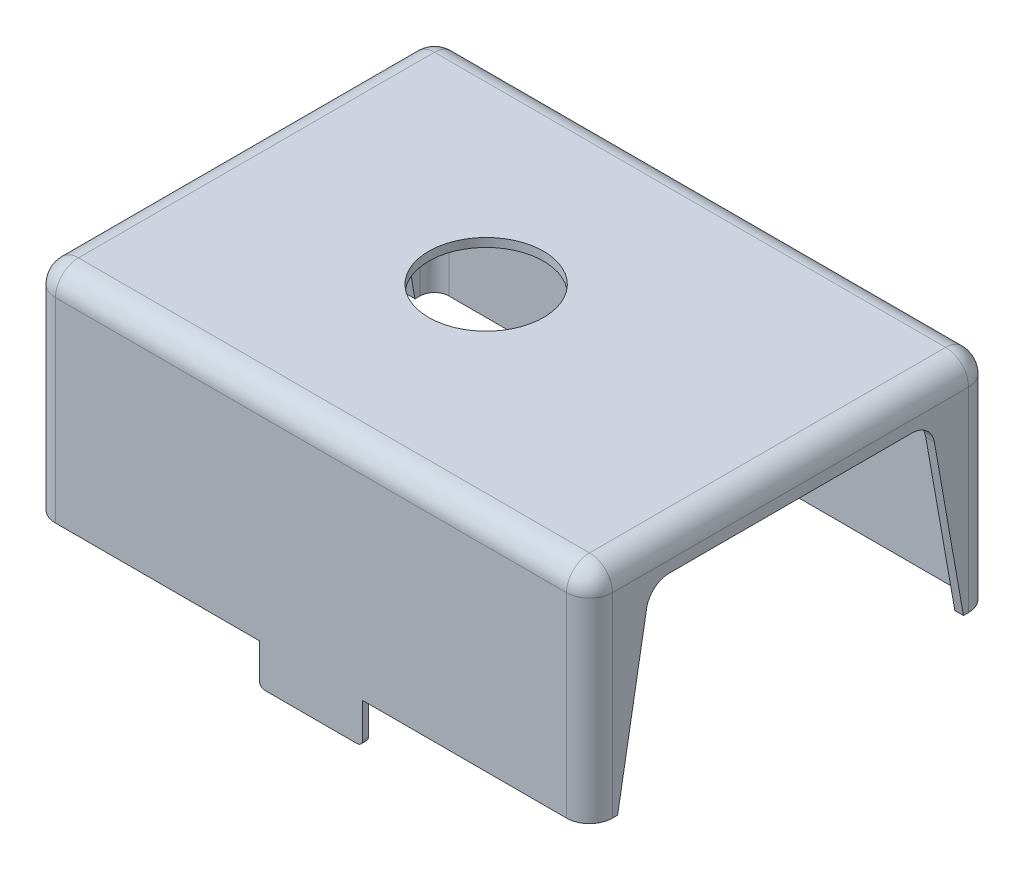
SolidWorks part; units mm, degrees
material "ABS"
ref_plane "Plano frontal" through (0, 0, 0) normal (0, 0, 1) x (1, 0, 0)
ref_plane "Plano superior" through (0, 0, 0) normal (0, 1, 0) x (1, 0, 0)
ref_plane "Plano direito" through (0, 0, 0) normal (1, 0, 0) x (0, 0, -1)
sketch "Esboço1" plane through (0, 0, 0) normal (0, 1, 0) x (1, 0, 0)
  line L0 (-48.5, 35) -> (48.5, -35) construction
  line L1 (-44.5, 35) -> (44.5, 35)
  line L2 (-48.5, 31) -> (-48.5, -31)
  line L3 (-44.5, -35) -> (44.5, -35)
  line L4 (48.5, 31) -> (48.5, -31)
  arc A0 (44.5, -35) -> (48.5, -31) centre (44.5, -31) ccw
  arc A1 (44.5, 35) -> (48.5, 31) centre (44.5, 31) cw
  arc A2 (-44.5, 35) -> (-48.5, 31) centre (-44.5, 31) ccw
  arc A3 (-48.5, -31) -> (-44.5, -35) centre (-44.5, -31) ccw
  point P11 (48.5, 35)
  point P17 (-48.5, -35)
  dimension "D3" = 4
  dimension "D1" = 97
  dimension "D2" = 70
extrude "Ressalto-extrusão1" add sketch "Esboço1" against normal blind 38
fillet "Filete1" radius 4 8 edges at (-47.3284, 0, -33.8284) (0, 0, -35) (47.3284, 0, -33.8284) (48.5, 0, 0) (47.3284, 0, 33.8284) (0, 0, 35) (-47.3284, 0, 33.8284) (-48.5, 0, 0)
shell "Casca1" thickness 1.5
sketch "Esboço2" plane through (0, 0, 0) normal (1, 0, 0) x (0, 0, -1)
  line L1 (-21.1107, -6) -> (21.1107, -6)
  line L2 (-25.05, -9.3054) -> (-31, -43.0497)
  line L3 (-31, -43.0497) -> (31, -43.0497)
  line L4 (25.05, -9.3054) -> (31, -43.0497)
  arc A0 (-21.1107, -6) -> (-25.05, -9.3054) centre (-21.1107, -10) ccw
  arc A1 (21.1107, -6) -> (25.05, -9.3054) centre (21.1107, -10) cw
  dimension "D6" = 4
  dimension "D1" = 62
  dimension "D2" = 100
  dimension "D3" = 100
  dimension "D4" = 31
  dimension "D5" = 6
extrude "Corte-extrusão1" cut sketch "Esboço2" against normal mid plane 100
sketch "Esboço3" plane through (0, -1.5, 0) normal (0, -1, 0) x (1, 0, 0)
  line L0 (-48.5, 21.1107) -> (-48.5, -21.1107) construction
  line L4 (-44.5, 35) -> (44.5, 35) construction
  line L5 (44.5, -35) -> (-44.5, -35) construction
  line L6 (48.5, -21.1107) -> (48.5, 21.1107) construction
  circle A0 centre (-28, 15) radius 2
  circle A1 centre (-28, 15) radius 1
  circle A2 centre (-28, -15) radius 1
  circle A3 centre (28, 15) radius 1
  circle A4 centre (28, -15) radius 1
  circle A5 centre (28, 15) radius 2
  circle A6 centre (28, -15) radius 2
  circle A7 centre (-28, -15) radius 2
  dimension "D3" = 2
  dimension "D4" = 4
  dimension "D5" = 2
  dimension "D6" = 2
  dimension "D7" = 2
  dimension "D8" = 20.5
  dimension "D9" = 20
  dimension "D10" = 20
  dimension "D11" = 20.5
  dimension "D13" = 20
  dimension "D1" = 20.5
  dimension "D2" = 20
  dimension "D12" = 20.5
extrude "Ressalto-extrusão2" add sketch "Esboço3" along normal blind 5 draft 2
sketch "Esboço4" plane through (0, 0, 35) normal (0, 0, 1) x (1, 0, 0)
  line L0 (-44.5, -38) -> (44.5, -38) construction
  line L1 (-9, -38) -> (9, -38)
  line L2 (-9, -38) -> (-9, -44)
  line L3 (-8, -45) -> (8, -45)
  line L4 (9, -38) -> (9, -44)
  arc A0 (8, -45) -> (9, -44) centre (8, -44) ccw
  arc A1 (-9, -44) -> (-8, -45) centre (-8, -44) ccw
  point P9 (9, -45)
  point P12 (-9, -45)
  dimension "D4" = 1
  dimension "D1" = 18
  dimension "D2" = 9
  dimension "D3" = 7
extrude "Ressalto-extrusão3" add sketch "Esboço4" against normal blind 1
sketch "Esboço5" plane through (0, 0, 0) normal (1, 0, 0) x (0, 0, -1)
  line L0 (-34, -40) -> (-32.5, -40)
  line L1 (-34, -44) -> (-34, -38) construction
  line L2 (-32.5, -40) -> (-32.5, -40.5)
  line L3 (-32.5, -40.5) -> (-34, -42)
  line L4 (-34, -42) -> (-34, -40)
  line L5 (-34, -45) -> (-35, -45) construction
  dimension "D1" = 5
  dimension "D2" = 2
  dimension "D3" = 1.5
  dimension "D4" = 0.5
extrude "Ressalto-extrusão4" add sketch "Esboço5" along normal mid plane 11
mirror "Espelhar1" about plane through (0, 0, 0) normal (0, 0, 1) of "Ressalto-extrusão4", "Ressalto-extrusão3"
sketch "Esboço6" plane through (0, 0, 0) normal (0, 1, 0) x (1, 0, 0)
  circle A0 centre (-5, 0.5) radius 10
  dimension "D2" = 0.5
  dimension "D3" = 5
  dimension "D1" = 20
extrude "Corte-extrusão2" cut sketch "Esboço6" against normal through all
equation "\"D4@Esboço2\" = \"D1@Esboço2\"/2"
equation "\"D2@Esboço4\" = \"D1@Esboço4\"/2"
